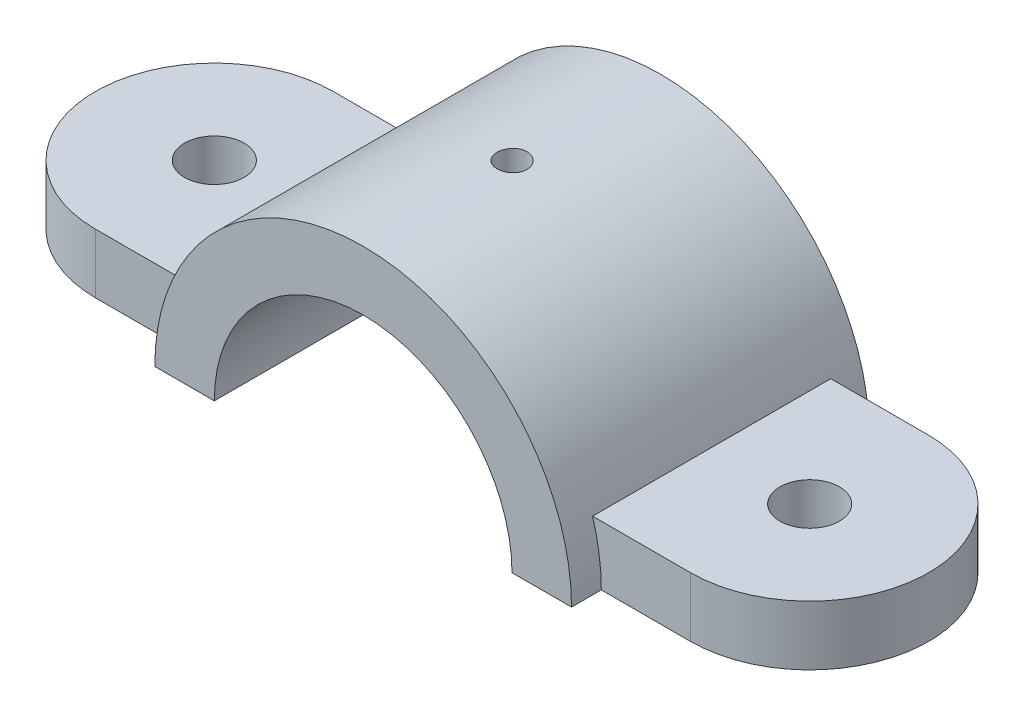
SolidWorks part; units mm, degrees
ref_plane "Front Plane" through (0, 0, 0) normal (0, 0, 1) x (1, 0, 0)
ref_plane "Top Plane" through (0, 0, 0) normal (0, 1, 0) x (1, 0, 0)
ref_plane "Right Plane" through (0, 0, 0) normal (1, 0, 0) x (0, 0, -1)
sketch "Sketch1" plane through (0, 0, 0) normal (0, 1, 0) x (1, 0, 0)
  line L0 (0, -32.5258) -> (0, 34.5946) construction
  line L1 (-63.5, 25.4) -> (63.5, 25.4)
  line L2 (63.5, -25.4) -> (-63.5, -25.4)
  arc A0 (63.5, 25.4) -> (63.5, -25.4) centre (63.5, 0) cw
  arc A1 (-63.5, 25.4) -> (-63.5, -25.4) centre (-63.5, 0) ccw
  circle A2 centre (-63.5, 0) radius 6.35
  circle A3 centre (63.5, 0) radius 6.35
  point P6 (0, 25.4)
  point P11 (0, -25.4)
  dimension "D1" = 25.4
  dimension "D2" = 12.7
  dimension "D3" = 127
extrude "base " add sketch "Sketch1" along normal blind 12.7
sketch "Sketch2" plane through (0, 0, 0) normal (0, 0, 1) x (1, 0, 0)
  line L0 (44.45, 0) -> (-44.45, 0)
  circle A0 centre (0, 0) radius 44.45
  dimension "D1" = 88.9
extrude "main body" add sketch "Sketch2" along normal mid plane 63.5 contours L0 A0
sketch "Sketch3" plane through (0, 0, 31.75) normal (0, 0, 1) x (1, 0, 0)
  line L0 (44.45, 0) -> (-44.45, 0) construction
  line L1 (-25.4, 0) -> (25.4, 0)
  line L2 (-25.4, 0) -> (-25.4, 25.4)
  line L3 (-25.4, 25.4) -> (25.4, 25.4)
  line L4 (25.4, 0) -> (25.4, 25.4)
  dimension "D1" = 25.4
  dimension "D2" = 50.8
  dimension "D3" = 25.4
extrude "rect cut " [suppressed] cut sketch "Sketch3" against normal through all
hole_wizard "center drill " positions "Sketch4" profile "Sketch6" hole size "1/4" standard "ANSI Inch" end condition through all
sketch "Sketch4" plane through (0, 0, 0) normal (0, -1, 0) x (-1, 0, 0)
  point P0 (0, 0)
sketch "Sketch6" plane through (0, 0, 0) normal (1, 0, 0) x (0, 0, -1)
  line L0 (0, 0) -> (0, 44.45)
  line L1 (0, 44.45) -> (3.175, 44.45)
  line L2 (3.175, 44.45) -> (3.175, 0)
  line L5 (3.175, 0) -> (0, 0)
  line L11 (0, -6.35) -> (0, 107.95) construction
  dimension "Thru Hole Dia." = 6.35
  dimension "Thru Hole Depth" = 44.45
sketch "Sketch7" plane through (0, 0, 0) normal (0, 0, 1) x (1, 0, 0)
  circle A0 centre (0, 0) radius 31.75
  dimension "D1" = 63.5
extrude "circuler cut " cut sketch "Sketch7" against normal through all and the other way through all
